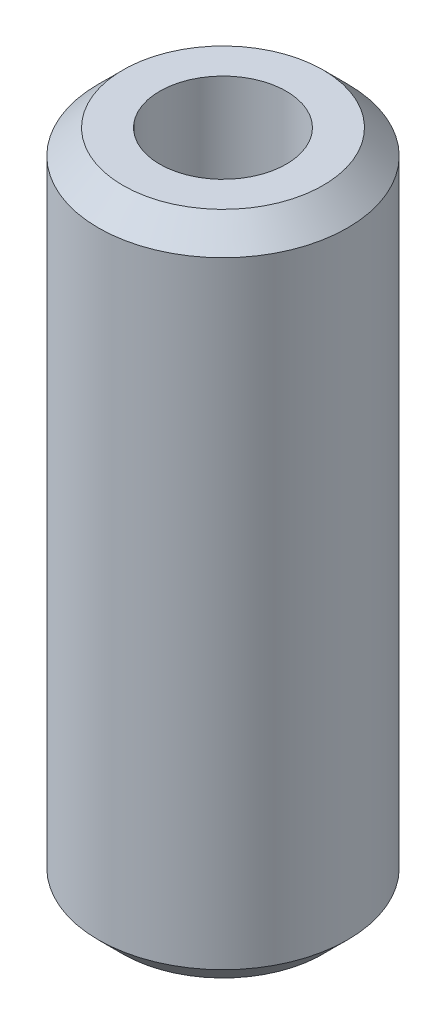
SolidWorks part; units mm, degrees
ref_plane "Płaszczyzna przednia" through (0, 0, 0) normal (0, 0, 1) x (1, 0, 0)
ref_plane "Płaszczyzna górna" through (0, 0, 0) normal (0, 1, 0) x (1, 0, 0)
ref_plane "Płaszczyzna prawa" through (0, 0, 0) normal (1, 0, 0) x (0, 0, -1)
sketch "Szkic1" plane through (0, 0, 0) normal (0, 1, 0) x (1, 0, 0)
  circle A0 centre (0, 0) radius 12.7
  circle A1 centre (0, 0) radius 6.45
  dimension "D1" = 25.4
  dimension "D2" = 12.9
extrude "Dodanie-wyciągnięcie1" add sketch "Szkic1" along normal blind 67.85
chamfer "Sfazowanie1" distance 2.5 angle 45 2 edges at (0, 0, 12.7) (0, 67.85, 12.7)
